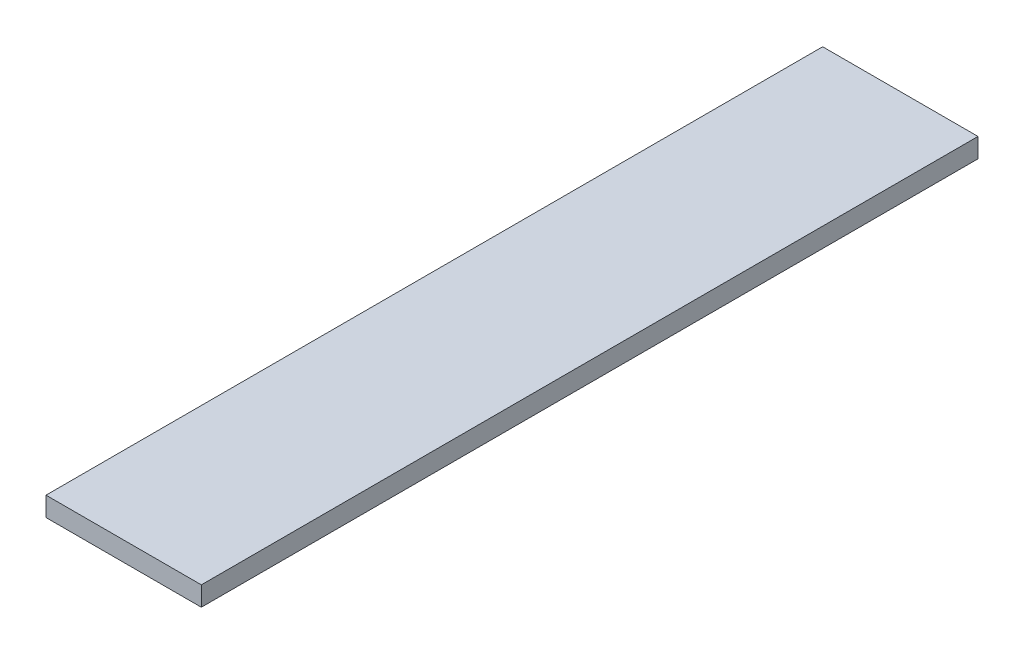
SolidWorks part; units mm, degrees
material "Teak"
ref_plane "Front Plane" through (0, 0, 0) normal (0, 0, 1) x (1, 0, 0)
ref_plane "Top Plane" through (0, 0, 0) normal (0, 1, 0) x (1, 0, 0)
ref_plane "Right Plane" through (0, 0, 0) normal (1, 0, 0) x (0, 0, -1)
sketch "Sketch1" plane through (0, 0, 0) normal (0, 1, 0) x (1, 0, 0)
  line L1 (0, 0) -> (25.4, 0)
  line L2 (0, 0) -> (0, 127)
  line L3 (0, 127) -> (25.4, 127)
  line L4 (25.4, 0) -> (25.4, 127)
  dimension "D1" = 127
  dimension "D2" = 25.4
extrude "Boss-Extrude1" add sketch "Sketch1" along normal blind 3.175 contours L4 L3 L2 L1
